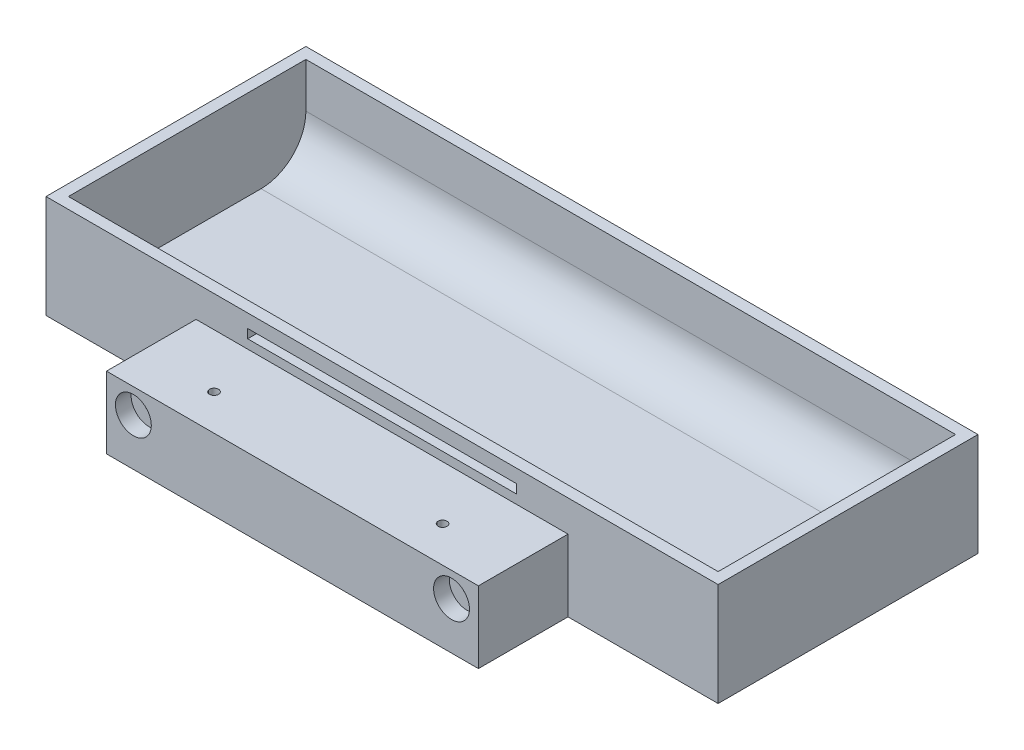
SolidWorks part; units mm, degrees
ref_plane "정면" through (0, 0, 0) normal (0, 0, 1) x (1, 0, 0)
ref_plane "윗면" through (0, 0, 0) normal (0, 1, 0) x (1, 0, 0)
ref_plane "우측면" through (0, 0, 0) normal (1, 0, 0) x (0, 0, -1)
sketch "스케치1" plane through (0, 0, 0) normal (0, 1, 0) x (1, 0, 0)
  line L1 (-41.5, 10) -> (41.5, 10)
  line L2 (-41.5, 10) -> (-41.5, -10)
  line L3 (-41.5, -10) -> (41.5, -10)
  line L4 (41.5, 10) -> (41.5, -10)
  line L5 (-41.5, 10) -> (41.5, -10) construction
  line L6 (-41.5, -10) -> (41.5, 10) construction
  point P0 (0, 0)
  dimension "D1" = 83
  dimension "D2" = 20
extrude "보스-돌출1" add sketch "스케치1" along normal blind 16
sketch "스케치2" plane through (0, 0, 10) normal (0, 0, 1) x (1, 0, 0)
  line L3 (-41.5, 16) -> (41.5, 16) construction
  line L4 (-41.5, 16) -> (-41.5, 0) construction
  line L6 (41.5, 16) -> (41.5, 0) construction
  circle A2 centre (-35.5, 10.5) radius 4
  circle A3 centre (35.5, 10.5) radius 4
  dimension "D1" = 8
  dimension "D2" = 8
  dimension "D4" = 5.5
  dimension "D5" = 6
  dimension "D6" = 6
extrude "컷-돌출1" cut sketch "스케치2" against normal blind 3.5
sketch "스케치3" plane through (0, 16, 0) normal (0, 1, 0) x (1, 0, 0)
  line L0 (-41.5, 10) -> (-41.5, -10) construction
  line L1 (-41.5, -10) -> (41.5, -10) construction
  line L2 (41.5, -10) -> (41.5, 10) construction
  circle A0 centre (-25.5, -2) radius 1
  circle A1 centre (25.5, -2) radius 1
  dimension "D1" = 2
  dimension "D2" = 16
  dimension "D3" = 8
  dimension "D4" = 16
  dimension "D5" = 8
extrude "컷-돌출2" cut sketch "스케치3" against normal blind 10
sketch "스케치6" plane through (0, 0, 6.5) normal (0, 0, 1) x (1, 0, 0)
  circle A0 centre (-35.5, 10.5) radius 1
  circle A1 centre (35.5, 10.5) radius 1
  dimension "D1" = 2
extrude "컷-돌출5" cut sketch "스케치6" against normal blind 8
sketch "스케치7" plane through (0, 0, -10) normal (0, 0, -1) x (-1, 0, 0)
  line L0 (0, 0) -> (0, 16) construction
  line L1 (-41.5, 16) -> (41.5, 16) construction
  line L2 (-41.5, 0) -> (41.5, 0) construction
  line L3 (-75, 3) -> (75, 3)
  line L4 (-75, 3) -> (-75, 0)
  line L5 (-75, 0) -> (75, 0)
  line L6 (75, 3) -> (75, 0)
  line L7 (-75, 3) -> (75, 0) construction
  line L8 (-75, 0) -> (75, 3) construction
  point P5 (0, 1.5)
  dimension "D1" = 150
  dimension "D2" = 3
extrude "보스-돌출2" add sketch "스케치7" along normal blind 58
sketch "스케치8" plane through (0, 3, 0) normal (0, 1, 0) x (1, 0, 0)
  line L0 (-72.5, 65.5) -> (-72.5, 12.5)
  line L1 (-75, 68) -> (75, 68)
  line L2 (-75, 68) -> (-75, 10)
  line L3 (-75, 10) -> (75, 10)
  line L4 (75, 68) -> (75, 10)
  line L5 (-72.5, 12.5) -> (72.5, 12.5)
  line L6 (72.5, 65.5) -> (72.5, 12.5)
  line L7 (-72.5, 65.5) -> (72.5, 65.5)
  dimension "D1" = 2.5
extrude "보스-돌출3" add sketch "스케치8" along normal blind 20
fillet "필렛1" radius 10 2 edges at (0, 3, -12.5) (0, 3, -65.5)
sketch "스케치9" plane through (-75, 0, 0) normal (-1, 0, 0) x (0, 0, 1)
  line L0 (-68, 0) -> (-68, 23) construction
  line L1 (-68, 18) -> (-66, 18)
  line L2 (-68, 18) -> (-68, 20)
  line L3 (-68, 20) -> (-66, 20)
  line L4 (-66, 18) -> (-66, 20)
  line L5 (-10, 0) -> (-10, 23) construction
  line L6 (-10, 18) -> (-12, 18)
  line L7 (-10, 18) -> (-10, 20)
  line L8 (-10, 20) -> (-12, 20)
  line L9 (-12, 18) -> (-12, 20)
  line L10 (-68, 23) -> (-10, 23) construction
  dimension "D1" = 2
  dimension "D2" = 2
  dimension "D3" = 2
  dimension "D4" = 2
  dimension "D5" = 3
  dimension "D6" = 3
extrude "컷-돌출6" cut sketch "스케치9" against normal blind 60 from offset 45
